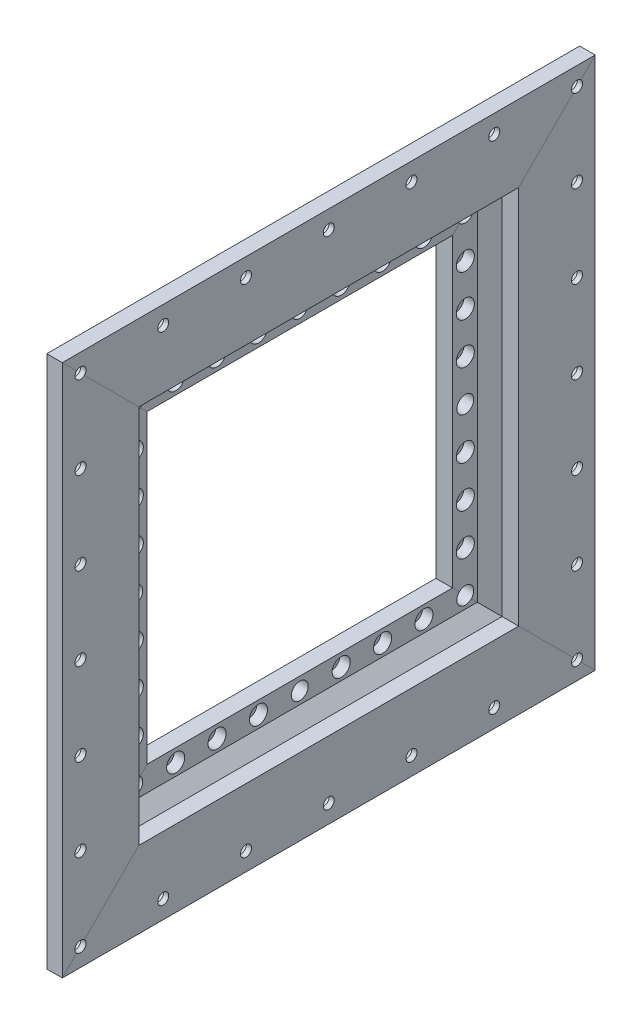
SolidWorks part; units mm, degrees
other "Markup1"
sketch "Sketch12" plane through (-15.24, -25.4, 25.4) normal (-0.7357, -0.6773, 0.0033) x (0.0323, -0.0303, 0.999)
ref_plane "Front Plane" through (0, 0, 0) normal (0, 0, 1) x (1, 0, 0)
ref_plane "Top Plane" through (0, 0, 0) normal (0, 1, 0) x (1, 0, 0)
ref_plane "Right Plane" through (0, 0, 0) normal (1, 0, 0) x (0, 0, -1)
sketch "Leg Sketch" plane through (0, 0, 0) normal (0, 0, 1) x (1, 0, 0)
  line L1 (19.05, 15.24) -> (8.89, 15.24)
  line L2 (8.89, 15.24) -> (1.27, 22.86)
  line L3 (1.27, 22.86) -> (1.27, 38.1)
  line L4 (1.27, 38.1) -> (-8.89, 38.1)
  line L5 (-8.89, 38.1) -> (-8.89, 25.4)
  line L6 (-8.89, 25.4) -> (-15.24, 19.05)
  line L7 (-15.24, 19.05) -> (-15.24, 15.24)
  line L8 (-15.24, 15.24) -> (0, 0)
  line L12 (9.525, 0) -> (9.525, -31.75)
  line L13 (9.525, -31.75) -> (19.05, -31.75)
  line L15 (0, 0) -> (9.525, 0)
  line L16 (19.05, -31.75) -> (19.05, 15.24)
  dimension "D1" = 12.7
  dimension "D2" = 10.16
  dimension "D3" = 15.24
  dimension "D4" = 10.7763
  dimension "D5" = 3.81
  dimension "D6" = 21.5526
  dimension "D7" = 31.75
  dimension "D8" = 15.24
  dimension "D9" = 10.16
  dimension "D10" = 9.525
  dimension "D12" = 9.525
sketch "Boundary" plane through (0, 0, 0) normal (-1, 0, 0) x (0, 0, 1)
  line L0 (0, 0) -> (-263.65, 0)
  line L3 (0, 0) -> (0, 263.65)
  line L4 (0, 263.65) -> (-263.65, 263.65)
  line L5 (-263.65, 263.65) -> (-263.65, 0)
  point P10 (-263.65, 0)
  point P13 (0, 0)
  dimension "D1" = 263.65
sweep "Frame" add profiles "Leg Sketch" path "Boundary"
sketch "Wall Screw Holes" plane through (0, 0, 0) normal (1, 0, 0) x (0, 0, -1)
  line L0 (38.1, 131.825) -> (225.55, 131.825) construction
  line L1 (225.55, 38.1) -> (225.55, 225.55) construction
  line L2 (131.825, 225.55) -> (131.825, 38.1) construction
  line L4 (38.1, 38.1) -> (225.55, 38.1) construction
  line L5 (38.1, 225.55) -> (38.1, 38.1) construction
  line L6 (225.55, 225.55) -> (38.1, 225.55) construction
  line L10 (19.05, 244.6) -> (19.05, 19.05) construction
  line L12 (19.05, 19.05) -> (244.6, 19.05) construction
  circle A0 centre (30.225, 55.63) radius 3.3782
  circle A1 centre (55.63, 30.23) radius 3.3782
  circle A2 centre (30.225, 81.03) radius 3.3782
  circle A3 centre (30.225, 106.43) radius 3.3782
  circle A5 centre (30.225, 157.23) radius 3.3782
  circle A6 centre (30.225, 182.63) radius 3.3782
  circle A7 centre (30.225, 208.03) radius 3.3782
  circle A8 centre (55.63, 233.43) radius 3.3782
  circle A9 centre (81.03, 233.43) radius 3.3782
  circle A10 centre (81.03, 30.23) radius 3.3782
  circle A11 centre (106.43, 233.43) radius 3.3782
  circle A12 centre (106.43, 30.23) radius 3.3782
  circle A15 centre (157.23, 233.43) radius 3.3782
  circle A16 centre (157.23, 30.23) radius 3.3782
  circle A17 centre (182.63, 233.43) radius 3.3782
  circle A18 centre (182.63, 30.23) radius 3.3782
  circle A19 centre (208.03, 233.43) radius 3.3782
  circle A20 centre (208.03, 30.23) radius 3.3782
  circle A21 centre (233.425, 81.03) radius 3.3782
  circle A22 centre (233.425, 55.63) radius 3.3782
  circle A23 centre (233.425, 106.43) radius 3.3782
  circle A25 centre (233.425, 157.23) radius 3.3782
  circle A26 centre (233.425, 182.63) radius 3.3782
  circle A27 centre (233.425, 208.03) radius 3.3782
  circle A29 centre (30.225, 233.43) radius 5.1945
  circle A30 centre (233.425, 233.43) radius 5.1945
  circle A31 centre (233.425, 30.23) radius 5.1945
  circle A32 centre (30.225, 30.23) radius 5.1945
  circle A33 centre (131.83, 233.43) radius 3.3782 [skipped]
  circle A34 centre (131.83, 30.23) radius 3.3782 [skipped]
  circle A35 centre (30.225, 131.83) radius 3.3782 [skipped]
  circle A36 centre (131.825, 233.43) radius 5.1945
  circle A37 centre (233.425, 131.825) radius 5.1945
  circle A38 centre (131.825, 30.23) radius 5.1945
  circle A39 centre (30.225, 131.825) radius 5.1945
  point P35 (0, 0)
  point P57 (0, 0)
  point P72 (131.825, 30.23)
  point P73 (131.825, 236.8277)
  point P74 (26.8676, 30.23)
  point P75 (0, 0)
  point P76 (0, 0)
  dimension "D3" = 6.7564
  dimension "D13" = 10.389
  dimension "D7" = 25.4
  dimension "D10" = 25.4
  dimension "D11" = 25.4
  dimension "D12" = 25.4
  dimension "D4" = 36.58
  dimension "D14" = 36.58
  dimension "D2" = 203.2
  dimension "D8" = 203.2
  dimension "D6" = 7
  dimension "D9" = 7
extrude "Free Fit Through Holes" cut sketch "Wall Screw Holes" along normal up to surface and the other way up to surface
hole_wizard "Wall Screws CBORE for 1/4 Socket Head Cap Screw1" positions "3DSketch1" profile "Sketch8" counterbore size "1/4" standard "ANSI Inch" end condition through all
sketch3d "3DSketch1"
  line L0 (1.27, 208.03, -30.225) -> (-8.89, 208.03, -30.225) construction
  line L1 (1.27, 182.63, -30.225) -> (-8.89, 182.63, -30.225) construction
  line L2 (1.27, 157.23, -30.225) -> (-8.89, 157.23, -30.225) construction
  line L4 (1.27, 106.43, -30.225) -> (-8.89, 106.43, -30.225) construction
  line L5 (1.27, 81.03, -30.225) -> (-8.89, 81.03, -30.225) construction
  line L6 (1.27, 55.63, -30.225) -> (-8.89, 55.63, -30.225) construction
  line L7 (1.27, 30.23, -55.63) -> (-8.89, 30.23, -55.63) construction
  line L8 (1.27, 30.23, -81.03) -> (-8.89, 30.23, -81.03) construction
  line L9 (1.27, 30.23, -208.03) -> (-8.89, 30.23, -208.03) construction
  line L10 (1.27, 30.23, -182.63) -> (-8.89, 30.23, -182.63) construction
  line L11 (1.27, 30.23, -157.23) -> (-8.89, 30.23, -157.23) construction
  line L13 (1.27, 30.23, -106.43) -> (-8.89, 30.23, -106.43) construction
  line L14 (1.27, 55.63, -233.425) -> (-8.89, 55.63, -233.425) construction
  line L15 (1.27, 81.03, -233.425) -> (-8.89, 81.03, -233.425) construction
  line L17 (1.27, 157.23, -233.425) -> (-8.89, 157.23, -233.425) construction
  line L18 (1.27, 182.63, -233.425) -> (-8.89, 182.63, -233.425) construction
  line L19 (1.27, 208.03, -233.425) -> (-8.89, 208.03, -233.425) construction
  line L20 (1.27, 233.43, -208.03) -> (-8.89, 233.43, -208.03) construction
  line L21 (1.27, 233.43, -182.63) -> (-8.89, 233.43, -182.63) construction
  line L22 (1.27, 233.43, -157.23) -> (-8.89, 233.43, -157.23) construction
  line L24 (1.27, 233.43, -106.43) -> (-8.89, 233.43, -106.43) construction
  line L25 (1.27, 233.43, -81.03) -> (-8.89, 233.43, -81.03) construction
  line L26 (1.27, 233.43, -55.63) -> (-8.89, 233.43, -55.63) construction
  line L27 (1.27, 106.43, -233.425) -> (-8.89, 106.43, -233.425) construction
  point P0 (1.27, 208.03, -30.225)
  point P4 (1.27, 182.63, -30.225)
  point P8 (1.27, 157.23, -30.225)
  point P16 (1.27, 106.43, -30.225)
  point P20 (1.27, 81.03, -30.225)
  point P24 (1.27, 55.63, -30.225)
  point P28 (1.27, 30.23, -55.63)
  point P32 (1.27, 30.23, -81.03)
  point P36 (1.27, 30.23, -208.03)
  point P40 (1.27, 30.23, -182.63)
  point P44 (1.27, 30.23, -157.23)
  point P52 (1.27, 30.23, -106.43)
  point P56 (1.27, 55.63, -233.425)
  point P60 (1.27, 81.03, -233.425)
  point P68 (1.27, 157.23, -233.425)
  point P72 (1.27, 182.63, -233.425)
  point P76 (1.27, 208.03, -233.425)
  point P80 (1.27, 233.43, -208.03)
  point P84 (1.27, 233.43, -182.63)
  point P88 (1.27, 233.43, -157.23)
  point P96 (1.27, 233.43, -106.43)
  point P100 (1.27, 233.43, -81.03)
  point P104 (1.27, 233.43, -55.63)
  point P109 (1.27, 106.43, -233.425)
sketch "Sketch8" plane through (1.27, 208.03, -30.225) normal (0, 1, 0) x (0, 0, -1)
  line L0 (0, 0) -> (0, 16.51)
  line L1 (0, 16.51) -> (3.3782, 16.51)
  line L3 (3.3782, 16.51) -> (3.3782, 6.35)
  line L4 (3.3782, 6.35) -> (5.5562, 6.35)
  line L5 (5.5562, 6.35) -> (5.5562, 0)
  line L7 (5.5562, 0) -> (0, 0)
  line L11 (0, -6.35) -> (0, 107.95) construction
  dimension "Thru Hole Dia." = 6.7564
  dimension "Thru Hole Depth" = 16.51
  dimension "C'Bore Dia." = 11.1125
  dimension "C'Bore Depth" = 6.35
sketch "Optical Table Holes" plane through (0, 0, 0) normal (-1, 0, 0) x (0, 0, 1)
  line L1 (-284.225, 284.225) -> (20.575, 284.225) construction
  line L4 (-295.4, 295.4) -> (-263.65, 263.65) construction
  line L5 (-295.4, 131.825) -> (31.75, 131.825) construction
  line L6 (-295.4, -31.75) -> (-295.4, 295.4) construction
  line L7 (31.75, 295.4) -> (31.75, -31.75) construction
  circle A0 centre (20.575, 284.225) radius 3.3782
  circle A47 centre (20.575, 284.225) radius 4.7625 construction
  circle A50 centre (-284.225, 284.225) radius 3.3782
  circle A52 centre (-284.225, 284.225) radius 4.7625 construction
  circle A53 centre (-30.225, 284.225) radius 3.3782
  circle A54 centre (-30.225, 284.225) radius 4.7625 construction
  circle A55 centre (-81.025, 284.225) radius 3.3782
  circle A56 centre (-81.025, 284.225) radius 4.7625 construction
  circle A57 centre (-131.825, 284.225) radius 3.3782
  circle A58 centre (-131.825, 284.225) radius 4.7625 construction
  circle A59 centre (-182.625, 284.225) radius 3.3782
  circle A60 centre (-182.625, 284.225) radius 4.7625 construction
  circle A61 centre (-233.425, 284.225) radius 3.3782
  circle A62 centre (-233.425, 284.225) radius 4.7625 construction
  circle A63 centre (-284.225, 233.425) radius 3.3782
  circle A64 centre (-284.225, 233.425) radius 4.7625 construction
  circle A65 centre (20.575, 233.425) radius 4.7625 construction
  circle A66 centre (20.575, 233.425) radius 3.3782
  circle A67 centre (-284.225, 182.625) radius 3.3782
  circle A68 centre (-284.225, 182.625) radius 4.7625 construction
  circle A69 centre (20.575, 182.625) radius 4.7625 construction
  circle A70 centre (20.575, 182.625) radius 3.3782
  circle A71 centre (-284.225, 131.825) radius 3.3782
  circle A72 centre (-284.225, 131.825) radius 4.7625 construction
  circle A73 centre (20.575, 131.825) radius 4.7625 construction
  circle A74 centre (20.575, 131.825) radius 3.3782
  circle A75 centre (-284.225, 81.025) radius 3.3782
  circle A76 centre (-284.225, 81.025) radius 4.7625 construction
  circle A77 centre (20.575, 81.025) radius 4.7625 construction
  circle A78 centre (20.575, 81.025) radius 3.3782
  circle A79 centre (-284.225, 30.225) radius 3.3782
  circle A80 centre (-284.225, 30.225) radius 4.7625 construction
  circle A81 centre (20.575, 30.225) radius 4.7625 construction
  circle A82 centre (20.575, 30.225) radius 3.3782
  circle A83 centre (-284.225, -20.575) radius 3.3782
  circle A84 centre (-284.225, -20.575) radius 4.7625 construction
  circle A85 centre (20.575, -20.575) radius 4.7625 construction
  circle A86 centre (20.575, -20.575) radius 3.3782
  circle A87 centre (-233.425, -20.575) radius 3.3782
  circle A88 centre (-233.425, -20.575) radius 4.7625 construction
  circle A89 centre (-182.625, -20.575) radius 3.3782
  circle A90 centre (-182.625, -20.575) radius 4.7625 construction
  circle A91 centre (-131.825, -20.575) radius 3.3782
  circle A92 centre (-131.825, -20.575) radius 4.7625 construction
  circle A93 centre (-81.025, -20.575) radius 3.3782
  circle A94 centre (-81.025, -20.575) radius 4.7625 construction
  circle A95 centre (-30.225, -20.575) radius 3.3782
  circle A96 centre (-30.225, -20.575) radius 4.7625 construction
  dimension "D3" = 6.7564
  dimension "D11" = 9.525
  dimension "D2" = 304.8
  dimension "D4" = 50.8
  dimension "D5" = 6
  dimension "D7" = 50.8
  dimension "D6" = 7
  dimension "D8" = 50.8
hole_wizard "CBORE for 1/4 Socket Head Cap Screw1" positions "3DSketch3" profile "Sketch14" counterbore size "1/4" standard "ANSI Inch" end condition through all
sketch3d "3DSketch3"
  point P0 (9.525, 284.225, -284.225)
sketch "Sketch14" plane through (9.525, 284.225, -284.225) normal (0, 1, 0) x (0, 0, 1)
  line L0 (0, 0) -> (0, 9.525)
  line L1 (0, 9.525) -> (3.3782, 9.525)
  line L3 (3.3782, 9.525) -> (3.3782, 6.35)
  line L4 (3.3782, 6.35) -> (5.5562, 6.35)
  line L5 (5.5562, 6.35) -> (5.5563, 0)
  line L7 (5.5563, 0) -> (0, 0)
  line L11 (0, -6.35) -> (0, 107.95) construction
  dimension "Thru Hole Dia." = 6.7564
  dimension "Thru Hole Depth" = 9.525
  dimension "C'Bore Dia." = 11.1125
  dimension "C'Bore Depth" = 6.35
pattern_linear "Optical Table CB Pattern" count 7 spacing 50.8 along (0, 0, 1) count 7 spacing 50.8 along (0, -1, 0) skipping (1, 1), (1, 2), (1, 3), (1, 4), (1, 5), (2, 1), (2, 2), (2, 3), (2, 4), (2, 5), (3, 1), (3, 2), (3, 3), (3, 4), (3, 5), (4, 1), (4, 2), (4, 3), (4, 4), (4, 5), (5, 1), (5, 2), (5, 3), (5, 4), (5, 5) of "CBORE for 1/4 Socket Head Cap Screw1"
equation "\"D14@Wall Screw Holes\"= \"D4@Wall Screw Holes\""
